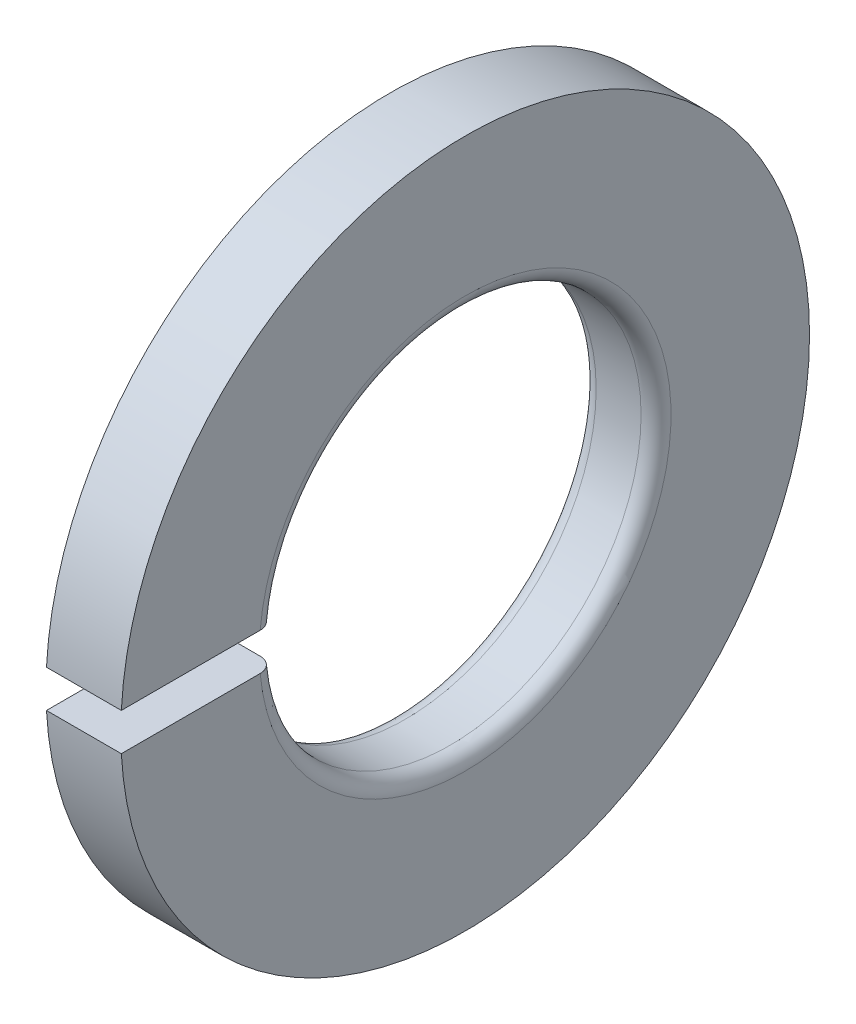
SolidWorks part; units mm, degrees
ref_plane "Plane1" through (0, 0, 0) normal (0, 0, 1) x (1, 0, 0)
ref_plane "Plane2" through (0, 0, 0) normal (0, 1, 0) x (1, 0, 0)
ref_plane "Plane3" through (0, 0, 0) normal (1, 0, 0) x (0, 0, -1)
sketch "Sketch1" plane through (0, 0, 0) normal (0, 0, 1) x (1, 0, 0)
  line L0 (-34.925, 0) -> (9.525, 0) construction
  line L1 (0, 2.75) -> (0, 4.6)
  line L2 (0, 4.6) -> (-1, 4.6)
  line L3 (-1, 4.6) -> (-1, 2.75)
  line L4 (-0.8, 2.55) -> (-0.2, 2.55)
  arc A0 (-0.8, 2.55) -> (-1, 2.75) centre (-0.8, 2.75) cw
  arc A1 (0, 2.75) -> (-0.2, 2.55) centre (-0.2, 2.75) cw
  point P8 (-1, 2.55)
  dimension "Fillet_rad" = 0.2
  dimension "D1" = 0.2
  dimension "Thickness" = 1
  dimension "Inside_dia" = 5.1
  dimension "Outside_dia" = 9.2
revolve "Base-Revolve" add sketch "Sketch1" angle 360 about L0
sketch "Sketch2" plane through (0, 0, 0) normal (-1, 0, 0) x (0, -1, 0)
  line L0 (-0.25, 0) -> (0.25, 0)
  line L1 (0, 0) -> (0, 12.7) construction
  line L2 (0.25, 0) -> (0.25, 4.692)
  line L3 (0.25, 4.692) -> (-0.25, 4.692)
  line L4 (-0.25, 4.692) -> (-0.25, 0)
  dimension "D1" = 0.5
  dimension "D2" = 4.692
extrude "Gap" cut sketch "Sketch2" along normal through all
equation "\"D1@Sketch1\" = \"Fillet_rad@Sketch1\""
equation "\"D1@Sketch2\" = \"Thickness@Sketch1\" * 0.5"
equation "\"D2@Sketch2\" = \"Outside_dia@Sketch1\" * 0.51"
